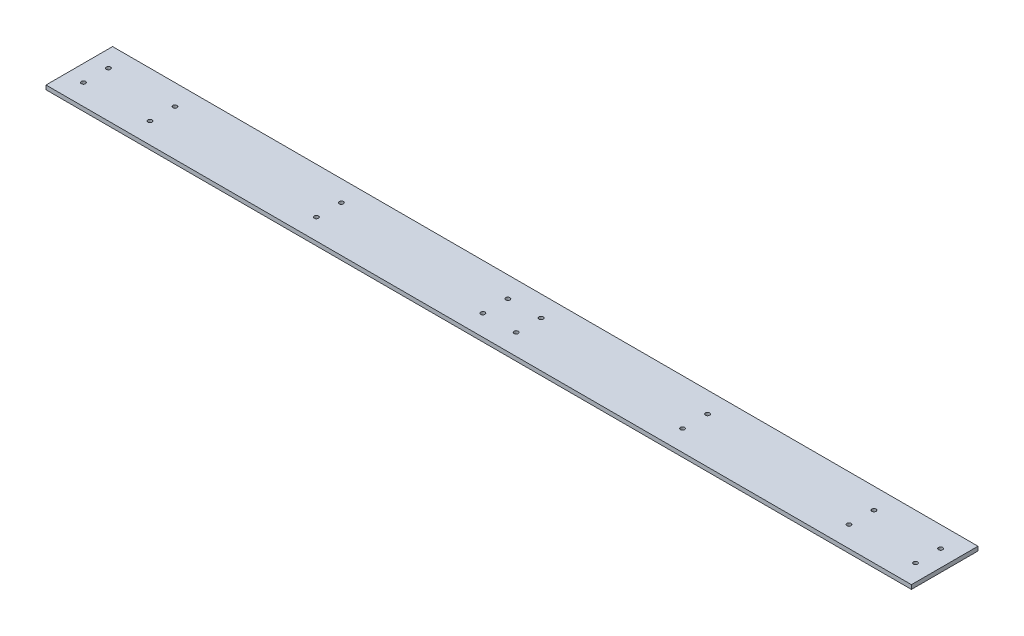
SolidWorks part; units mm, degrees
ref_plane "Front Plane" through (0, 0, 0) normal (0, 0, 1) x (1, 0, 0)
ref_plane "Top Plane" through (0, 0, 0) normal (0, 1, 0) x (1, 0, 0)
ref_plane "Right Plane" through (0, 0, 0) normal (1, 0, 0) x (0, 0, -1)
sketch "Sketch1" plane through (0, 0, 0) normal (0, 1, 0) x (1, 0, 0)
  line L0 (-200, 15) -> (-200, -15) construction
  line L1 (-500, 40) -> (540, 40)
  line L2 (-500, 40) -> (-500, -40)
  line L3 (-500, -40) -> (540, -40)
  line L4 (540, 40) -> (540, -40)
  line L5 (-200, 0) -> (0, 0) construction
  line L6 (0, 15) -> (0, -15) construction
  line L7 (240, 15) -> (240, -15) construction
  line L8 (0, 15) -> (40, 15) construction
  line L9 (40, 15) -> (40, -15) construction
  line L10 (40, -15) -> (0, -15) construction
  line L11 (0, 15) -> (-200, 15) construction
  line L12 (40, -15) -> (240, -15) construction
  line L13 (0, 0) -> (40, 0) construction
  line L14 (40, 0) -> (240, 0) construction
  line L15 (240, 0) -> (540, 0) construction
  line L16 (-200, 0) -> (-500, 0) construction
  line L17 (-400, 15) -> (-480, 15) construction
  line L18 (-480, 15) -> (-480, -15) construction
  line L19 (440, 15) -> (520, 15) construction
  line L20 (520, 15) -> (520, -15) construction
  circle A0 centre (0, 15) radius 2.5
  circle A1 centre (0, -15) radius 2.5
  circle A2 centre (40, 15) radius 2.5
  circle A3 centre (40, -15) radius 2.5
  circle A4 centre (-200, 15) radius 2.5
  circle A5 centre (-200, -15) radius 2.5
  circle A6 centre (240, -15) radius 2.5
  circle A7 centre (240, 15) radius 2.5
  circle A8 centre (-400, 15) radius 2.5
  circle A9 centre (-400, -15) radius 2.5
  circle A10 centre (440, -15) radius 2.5
  circle A11 centre (440, 15) radius 2.5
  circle A12 centre (520, 15) radius 2.5
  circle A13 centre (520, -15) radius 2.5
  circle A14 centre (-480, 15) radius 2.5
  circle A15 centre (-480, -15) radius 2.5
  dimension "D1" = 5
  dimension "D4" = 40
  dimension "D11" = 20
  dimension "D2" = 30
  dimension "D3" = 80
  dimension "D6" = 200
  dimension "D8" = 200
  dimension "D9" = 80
  dimension "D10" = 80
  dimension "D12" = 20
  dimension "D5" = 3
  dimension "D7" = 3
extrude "Boss-Extrude2" add sketch "Sketch1" along normal blind 5
equation "\"skin_sheetmetal_thickness\"= 0.80"
equation "\"base_width_skin_spacer\" = \"base_width_skin_target_width\" - 4 * \"skin_sheetmetal_thickness\" - 2 * \"base_width_skin_target_bend_radius\""
equation "\"base_width_skin_inner\" = \"base_width_skin_spacer\" + 2 * \"skin_sheetmetal_thickness\""
equation "\"base_width_skin_outer\" = \"base_width_skin_inner\" + 2 * \"skin_sheetmetal_thickness\""
equation "\"bend_cut_width\"= 3"
equation "\"bend_cut_length\"= 3"
equation "\"bend_offset_inner\"= 12.5"
equation "\"bend_offset_outer\" = \"bend_offset_inner\" + \"skin_sheetmetal_thickness\""
equation "\"border_offset_ends\"= 20"
equation "\"border_offset_sides\"= 10"
equation "\"border_offset_flange_horiz\"= 10"
equation "\"rivet_size\"= 4.3"
equation "\"rivet_offset_ends\"= \"rivet_spacing_horiz\"/2 - \"border_offset_ends\""
equation "\"rivet_spacing_horiz\"= 100"
equation "\"rivet_spacing_vert\"= 30"
equation "\"rivet_spacing_offset_right\"= 40"
equation "\"base_length\"= 200"
